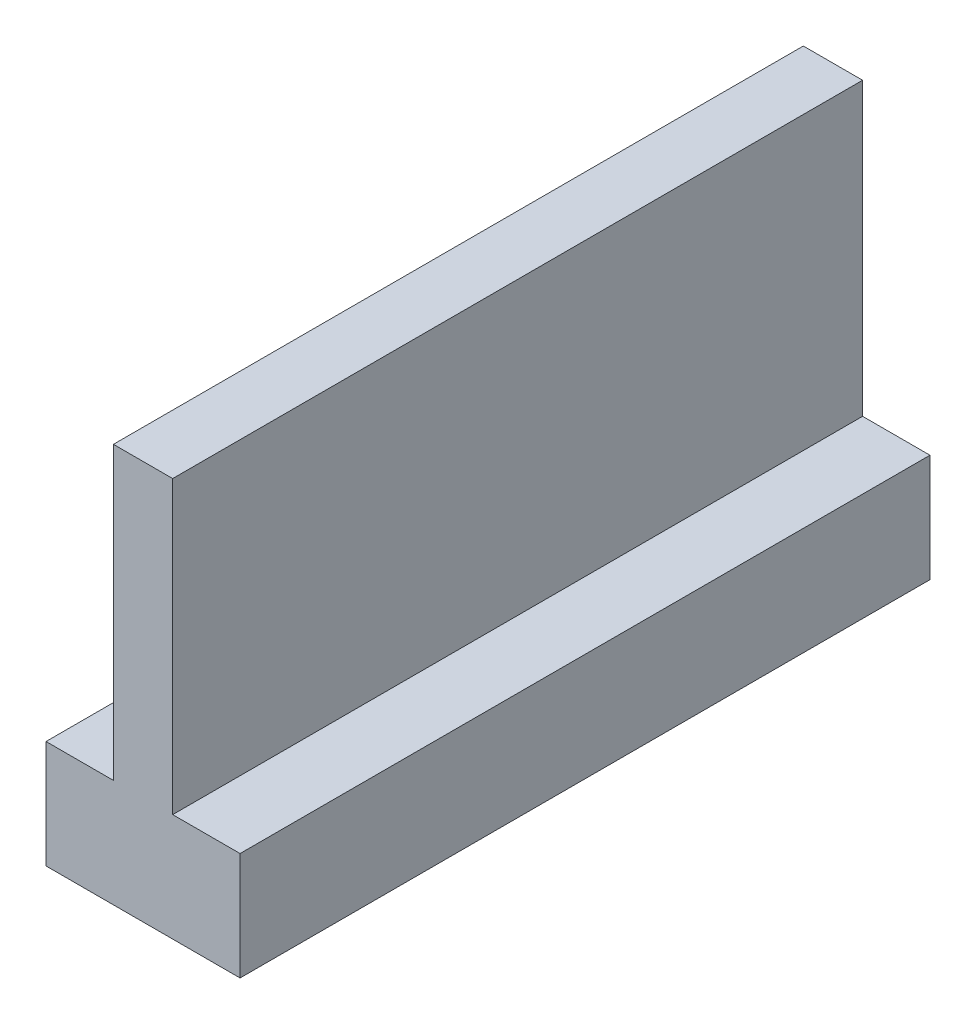
SolidWorks part; units mm, degrees
ref_plane "Front Plane" through (0, 0, 0) normal (0, 0, 1) x (1, 0, 0)
ref_plane "Top Plane" through (0, 0, 0) normal (0, 1, 0) x (1, 0, 0)
ref_plane "Right Plane" through (0, 0, 0) normal (1, 0, 0) x (0, 0, -1)
sketch "Sketch2" plane through (0, 0, 0) normal (0, 0, 1) x (1, 0, 0)
  line L0 (0, 0) -> (0, 10)
  line L1 (0, 10) -> (6.25, 10)
  line L2 (6.25, 10) -> (6.25, 37)
  line L8 (11.75, 37) -> (11.75, 10)
  line L9 (11.75, 10) -> (18, 10)
  line L10 (18, 10) -> (18, 0)
  line L11 (18, 0) -> (0, 0)
  line L12 (9, 0) -> (9, 37) construction
  line L13 (6.25, 37) -> (11.75, 37)
  point P6 (9, 31)
  dimension "D1" = 18
  dimension "D2" = 27
  dimension "D3" = 5.5
  dimension "D4" = 10
extrude "Boss-Extrude2" add sketch "Sketch2" along normal blind 64
